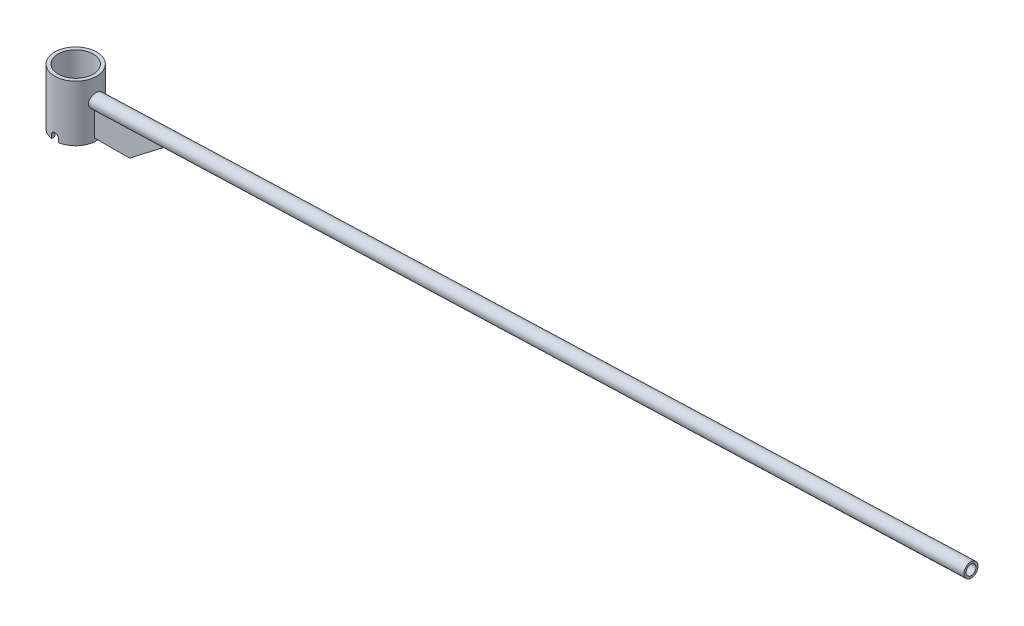
SolidWorks part; units mm, degrees
ref_plane "Спереди" through (0, 0, 0) normal (0, 0, 1) x (1, 0, 0)
ref_plane "Сверху" through (0, 0, 0) normal (0, 1, 0) x (1, 0, 0)
ref_plane "Справа" through (0, 0, 0) normal (1, 0, 0) x (0, 0, -1)
sketch "Эскиз1" plane through (0, 0, 0) normal (0, 1, 0) x (1, 0, 0)
  circle A0 centre (0, 0) radius 25
  circle A1 centre (0, 0) radius 30
  dimension "D1" = 50
  dimension "D2" = 60
extrude "Бобышка-Вытянуть1" add sketch "Эскиз1" along normal mid plane 80
sketch "Эскиз2" plane through (0, 0, 0) normal (0, 0, 1) x (1, 0, 0)
  line L0 (30, 10) -> (1280, 53.651)
  line L2 (30, -40) -> (30, 40) construction
  line L3 (-30, -40) -> (30, -40) construction
  dimension "D1" = 50
  dimension "D2" = 1250
  dimension "D3" = 92
ref_plane "Плоскость1" through (1280, 53.651, 0) normal (0.9994, 0.0349, 0) x (0, 0, -1)
sketch "Эскиз3" plane through (1280, 53.651, 0) normal (0.9994, 0.0349, 0) x (0, 0, -1)
  circle A0 centre (0, 0) radius 10
  circle A1 centre (0, 0) radius 7
  dimension "D1" = 20
  dimension "D2" = 14
extrude "Бобышка-Вытянуть2" add sketch "Эскиз3" against normal up to body separate body
sketch "Эскиз4" plane through (0, 0, 0) normal (0, 0, 1) x (1, 0, 0)
  line L0 (30, -40) -> (30, 40) construction
  line L1 (30, -35) -> (30, 0)
  line L2 (30, -0.0061) -> (1280.349, 43.6571) construction
  line L3 (30, 0) -> (130, 3.486)
  line L4 (30, -35) -> (80, -35)
  line L5 (80, -35) -> (130, 3.486)
  dimension "D1" = 50
  dimension "D2" = 35
  dimension "D3" = 100
extrude "Бобышка-Вытянуть3" add sketch "Эскиз4" along normal mid plane 6 separate body
sketch "Эскиз5" plane through (0, 0, 0) normal (0, 0, 1) x (1, 0, 0)
  line L0 (-5, -35) -> (-5, -62)
  line L1 (-5, -62) -> (5, -62)
  line L2 (5, -62) -> (5, -35)
  line L7 (-30, -40) -> (30, -40) construction
  arc A0 (5, -35) -> (-5, -35) centre (0, -35) ccw
  dimension "D1" = 10
  dimension "D2" = 10
  dimension "D3" = 32
extrude "Вырез-Вытянуть1" cut sketch "Эскиз5" along normal through all and the other way through all
sketch "Эскиз6" plane through (0, 0, 0) normal (0, 0, 1) x (1, 0, 0)
  line L0 (1279.651, 63.6449) -> (30, 20.0061) construction
  line L1 (1279.651, 63.6449) -> (30, 20.0061) construction
